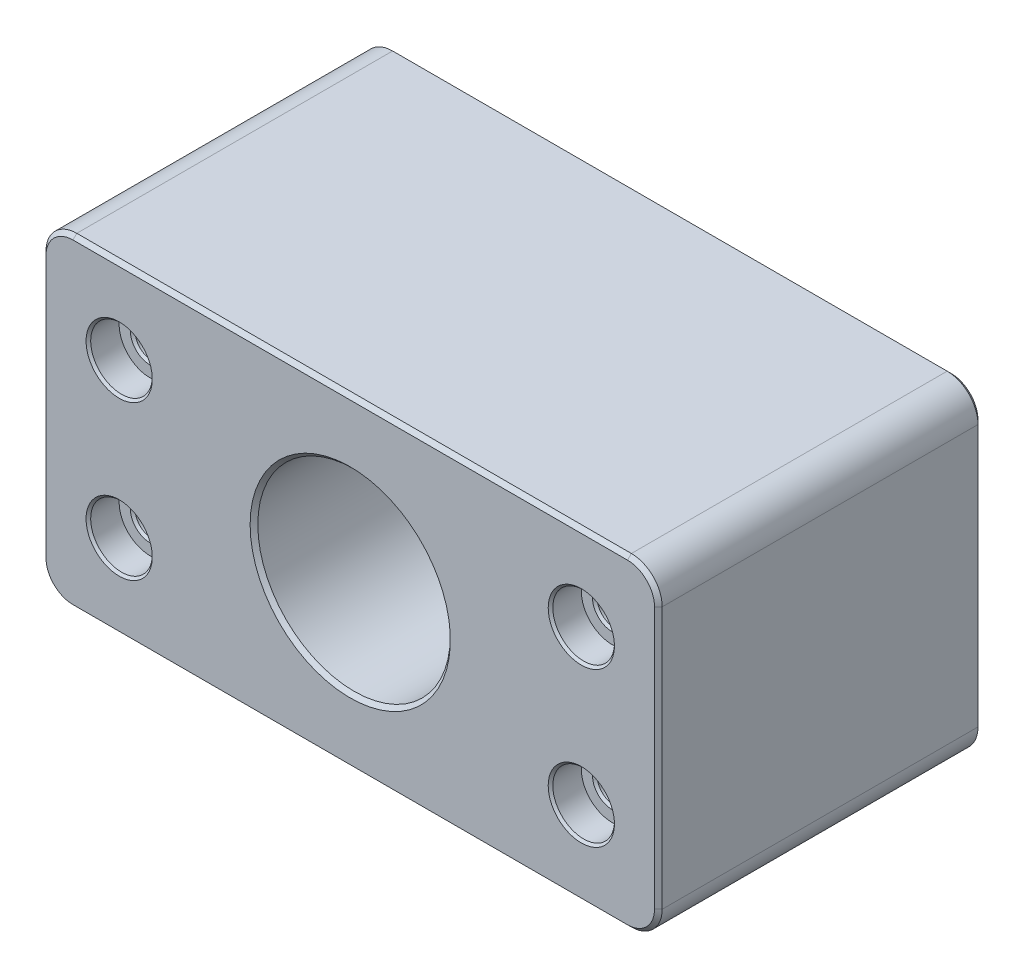
SolidWorks part; units mm, degrees
material "HDPE, Black"
ref_plane "Front Plane" through (0, 0, 0) normal (0, 0, 1) x (1, 0, 0)
ref_plane "Top Plane" through (0, 0, 0) normal (0, 1, 0) x (1, 0, 0)
ref_plane "Right Plane" through (0, 0, 0) normal (1, 0, 0) x (0, 0, -1)
sketch "Sketch1" plane through (0, 0, 0) normal (0, 0, 1) x (1, 0, 0)
  line L1 (-40, -21) -> (40, -21)
  line L2 (-40, -21) -> (-40, 21)
  line L3 (-40, 21) -> (40, 21)
  line L4 (40, -21) -> (40, 21)
  line L5 (-40, -21) -> (40, 21) construction
  line L6 (-40, 21) -> (40, -21) construction
  point P0 (0, 0)
  dimension "D1" = 80
  dimension "D2" = 42
extrude "Boss-Extrude1" add sketch "Sketch1" along normal blind 42
fillet "Fillet1" radius 4 4 edges at (40, -21, 21) (-40, -21, 21) (40, 21, 21) (-40, 21, 21)
chamfer "Chamfer1" distance 0.5 angle 45 16 edges at (0, -21, 42) (38.8284, -19.8284, 42) (-38.8284, -19.8284, 42) (40, 0, 42) (-40, 0, 42) (38.8284, 19.8284, 42) (-38.8284, 19.8284, 42) (0, 21, 42) (0, -21, 0) (38.8284, -19.8284, 0) (-38.8284, -19.8284, 0) (40, 0, 0) (-40, 0, 0) (38.8284, 19.8284, 0) (-38.8284, 19.8284, 0) (0, 21, 0)
sketch "Sketch2" plane through (0, 0, 42) normal (0, 0, 1) x (1, 0, 0)
  line L3 (-30, -10) -> (30, -10)
  line L4 (-30, -10) -> (-30, 10)
  line L5 (-30, 10) -> (30, 10)
  line L6 (30, -10) -> (30, 10)
  line L7 (-30, -10) -> (30, 10) construction
  line L8 (-30, 10) -> (30, -10) construction
  point P1 (0, 0)
  dimension "D1" = 60
  dimension "D2" = 20
hole_wizard "CBORE for M4 SHCS1" positions "Sketch3" profile "Sketch4" counterbore size "M4" standard "ANSI Metric" end condition through all
sketch "Sketch3" plane through (0, 0, 42) normal (0, 0, 1) x (1, 0, 0)
  point P7 (-30, 10)
  point P10 (30, 10)
  point P13 (30, -10)
  point P16 (-30, -10)
sketch "Sketch4" plane through (-30, 10, 42) normal (1, 0, 0) x (0, -1, 0)
  line L0 (0, 0) -> (0, 42)
  line L1 (0, 42) -> (2.25, 42)
  line L3 (2.25, 42) -> (2.25, 4)
  line L4 (2.25, 4) -> (4, 4)
  line L5 (4, 4) -> (4, 0)
  line L7 (4, 0) -> (0, 0)
  line L11 (0, -6.35) -> (0, 107.95) construction
  dimension "Thru Hole Dia." = 4.5
  dimension "Thru Hole Depth" = 42
  dimension "C'Bore Dia." = 8
  dimension "C'Bore Depth" = 4
sketch "Sketch5" plane through (0, 0, 0) normal (0, 0, -1) x (-1, 0, 0)
  circle A0 centre (0, 0) radius 12.5
  dimension "D1" = 25
extrude "Cut-Extrude2" cut sketch "Sketch5" against normal through all
chamfer "Chamfer2" distance 0.5 angle 45 2 edges at (-12.5, 0, 0) (-12.5, 0, 42)
chamfer "Chamfer3" distance 0.3 angle 45 12 edges at (-27.75, -10, 38) (-27.75, -10, 0) (32.25, -10, 38) (32.25, -10, 0) (32.25, 10, 38) (32.25, 10, 0) (-27.75, 10, 38) (-27.75, 10, 0) (-26, -10, 42) (34, -10, 42) (34, 10, 42) (-26, 10, 42)
